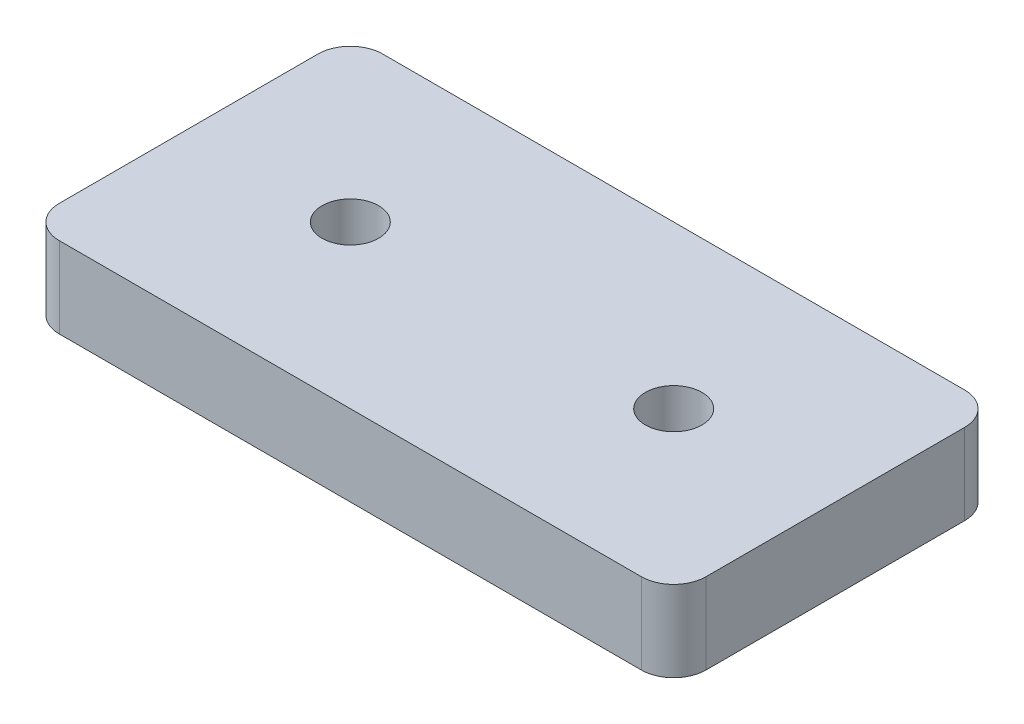
SolidWorks part; units mm, degrees
ref_plane "前视基准面" through (0, 0, 0) normal (0, 0, 1) x (1, 0, 0)
ref_plane "上视基准面" through (0, 0, 0) normal (0, 1, 0) x (1, 0, 0)
ref_plane "右视基准面" through (0, 0, 0) normal (1, 0, 0) x (0, 0, -1)
sketch "草图1" plane through (0, 0, 0) normal (0, 1, 0) x (1, 0, 0)
  line L0 (-30.7116, 0) -> (43.6324, 0) construction
  line L1 (0, -15.1219) -> (0, 29.1681) construction
  line L2 (-10, -10) -> (-10, 50)
  line L3 (30, -10) -> (-30, -10)
  line L4 (30, -10) -> (30, 10)
  line L5 (30, 10) -> (-12.3236, 10)
  line L6 (-30, -10) -> (-30, 10)
  line L7 (30, -10) -> (-30, 10) construction
  line L8 (30, 10) -> (-30, -10) construction
  line L9 (-10, -10) -> (10, -10)
  line L11 (-10, 50) -> (10, 50)
  line L13 (-10, 10) -> (-30, 10)
  line L14 (10, 10) -> (10, 50)
  circle A0 centre (0, 0) radius 1.75
  circle A1 centre (-20, 0) radius 1.75
  circle A2 centre (20, 0) radius 1.75
  circle A3 centre (0, 20) radius 1.75
  circle A4 centre (0, 40) radius 1.75
  dimension "D1" = 3.5
  dimension "D4" = 20
  dimension "D5" = 20
  dimension "D9" = 40
  dimension "D10" = 20
  dimension "D2" = 20
  dimension "D3" = 60
  dimension "D8" = 10
extrude "凸台-拉伸1" add sketch "草图1" along normal blind 5 contours L5 L14 L11 L2 L13 L6 L3 L4 A4 A3 A2 A1 A0
fillet "圆角1" radius 2 2 edges at (30, 2.5, 10) (30, 2.5, -10)
fillet "圆角2" radius 2 1 edges at (-10, 2.5, 10)
fillet "圆角3" radius 2 1 edges at (-10, 2.5, -10)
